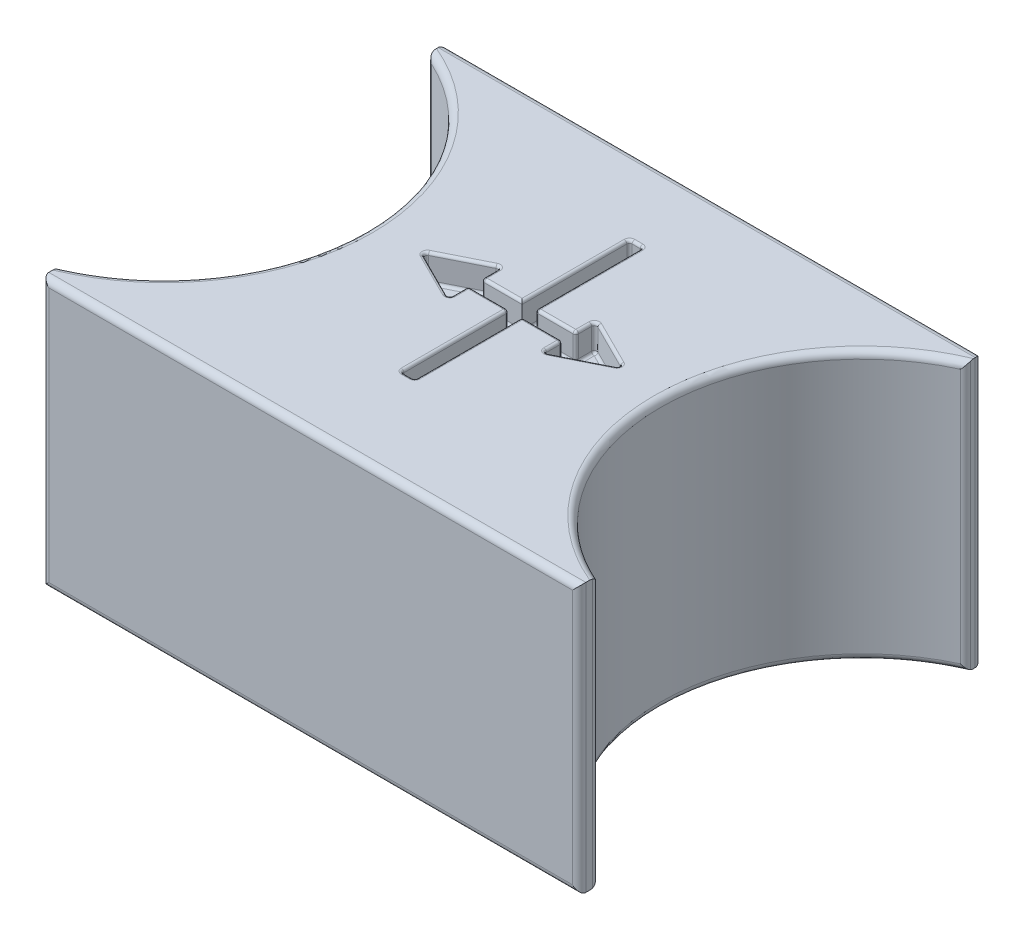
SolidWorks part; units mm, degrees
ref_plane "Front Plane" through (0, 0, 0) normal (0, 0, 1) x (1, 0, 0)
ref_plane "Top Plane" through (0, 0, 0) normal (0, 1, 0) x (1, 0, 0)
ref_plane "Right Plane" through (0, 0, 0) normal (1, 0, 0) x (0, 0, -1)
sketch "Sketch1" plane through (0, 0, 0) normal (0, 1, 0) x (1, 0, 0)
  line L1 (-20, 0) -> (0, 0)
  line L2 (-20, 0) -> (-20, -15)
  line L3 (-20, -15) -> (0, -15)
  line L4 (0, 0) -> (0, -15)
  dimension "D1" = 20
  dimension "D2" = 15
  dimension "D3" = 0
  dimension "D4" = 0
extrude "Boss-Extrude1" add sketch "Sketch1" along normal blind 10
sketch "Sketch2" plane through (0, 10, 0) normal (0, 1, 0) x (1, 0, 0)
  line L1 (-10, 3.763) -> (-10, -18.2775) construction
  circle A4 centre (-22.9984, -7.4588) radius 7.5
  circle A5 centre (2.9984, -7.4588) radius 7.5
  point P2 (-20, 0)
  point P3 (-20, -15)
  point P7 (-22.4295, -7.5408)
  point P10 (-23.0386, -7.4594)
  point P11 (-10, -7.2573)
  point P14 (3.78, -15)
  point P15 (3.78, 0)
  dimension "D1" = 15
  dimension "D3" = 10
  dimension "D2" = 13
extrude "Cut-Extrude1" cut sketch "Sketch2" against normal blind 10
fillet "Fillet1" radius 0.25 16 edges at (-10, 0, 0) (-10, 0, 15) (-15.4984, 0, 7.4588) (-15.4984, 10, 7.4588) (-10, 10, 0) (-10, 10, 15) (0, 5, 0) (-20, 5, 0) (-20, 5, 15) (0, 5, 15) (0, 5, 0.5842) (0, 5, 14.3333) (-4.5016, 10, 7.4588) (-4.5016, 0, 7.4588) (-20, 5, 14.3333) (-20, 5, 0.5842)
sketch "Sketch3" plane through (0, 0, 0) normal (0, -1, 0) x (1, 0, 0)
  circle A0 centre (-10, 7.5) radius 2.5
  dimension "D3" = 5
  dimension "D1" = 10
  dimension "D2" = 7.5
extrude "Cut-Extrude2" cut sketch "Sketch3" against normal blind 8
fillet "Fillet2" radius 2 1 edges at (-10, 8, 5)
sketch "Sketch4" plane through (0, 10, 0) normal (0, 1, 0) x (1, 0, 0)
  line L0 (-9.75, -7.375) -> (-8.25, -7.375)
  line L1 (-10.25, -2.875) -> (-9.75, -2.875)
  line L2 (-10.25, -2.875) -> (-10.25, -6.875)
  line L3 (-10.25, -11.375) -> (-9.75, -11.375)
  line L4 (-9.75, -2.875) -> (-9.75, -6.875)
  line L5 (-9.75, -6.875) -> (-8.25, -6.875)
  line L6 (-11.75, -6.125) -> (-11.75, -6.875)
  line L7 (-10.25, -6.875) -> (-11.75, -6.875)
  line L9 (-10.25, -7.375) -> (-11.75, -7.375)
  line L15 (-11.75, -8.125) -> (-13.75, -7.125)
  line L16 (-13.75, -7.125) -> (-11.75, -6.125)
  line L17 (-10, -2.1517) -> (-10, -12.0668) construction
  line L18 (-6.25, -7.125) -> (-8.25, -6.125)
  line L19 (-8.25, -8.125) -> (-6.25, -7.125)
  line L21 (-8.25, -6.125) -> (-8.25, -6.875)
  line L22 (-9.75, -7.375) -> (-9.75, -11.375)
  line L23 (-10.25, -7.375) -> (-10.25, -11.375)
  line L24 (-11.75, -7.375) -> (-11.75, -8.125)
  line L25 (-8.25, -7.375) -> (-8.25, -8.125)
  point P15 (-11, -7.375)
  point P18 (-9, -7.375)
  dimension "D1" = 0.5
  dimension "D2" = 9.75
  dimension "D3" = 8.5
  dimension "D4" = 2.875
  dimension "D5" = 0.5
  dimension "D8" = 4
  dimension "D9" = 1.5
  dimension "D11" = 2
  dimension "D12" = 0.75
  dimension "D13" = 2
  dimension "D14" = 1
extrude "Cut-Extrude3" cut sketch "Sketch4" against normal blind 1
fillet "Fillet3" radius 0.1 53 edges at (-8.25, 9.5, 6.125) (-11, 10, 6.875) (-12.75, 10, 7.625) (-10.25, 10, 9.375) (-9.75, 10, 9.375) (-7.25, 10, 6.625) (-8.25, 10, 6.5) (-9.75, 10, 4.875) (-10.25, 10, 4.875) (-9.75, 9.5, 2.875) (-10.25, 9.5, 2.875) (-10, 10, 2.875) (-10.25, 9.5, 11.375) (-9.75, 9.5, 11.375) (-10, 10, 11.375) (-10.25, 9.5, 7.375) (-11, 10, 7.375) (-9.75, 9.5, 7.375) (-9, 10, 7.375) (-6.25, 9.5, 7.125) (-7.25, 10, 7.625) (-8.25, 9.5, 7.375) (-8.25, 9.5, 8.125) (-8.25, 10, 7.75) (-8.25, 9.5, 6.875) (-9.75, 9.5, 6.875) (-9, 10, 6.875) (-13.75, 9.5, 7.125) (-12.75, 10, 6.625) (-11.75, 9.5, 6.875) (-11.75, 9.5, 6.125) (-11.75, 10, 6.5) (-11.75, 9.5, 8.125) (-11.75, 9.5, 7.375) (-11.75, 10, 7.75) (-10, 9, 2.875) (-9.75, 9, 4.875) (-9, 9, 6.875) (-8.25, 9, 6.5) (-7.25, 9, 6.625) (-7.25, 9, 7.625) (-8.25, 9, 7.75) (-9, 9, 7.375) (-9.75, 9, 9.375) (-10, 9, 11.375) (-10.25, 9, 9.375) (-11, 9, 7.375) (-11.75, 9, 7.75) (-12.75, 9, 7.625) (-12.75, 9, 6.625) (-11.75, 9, 6.5) (-11, 9, 6.875) (-10.25, 9, 4.875)
